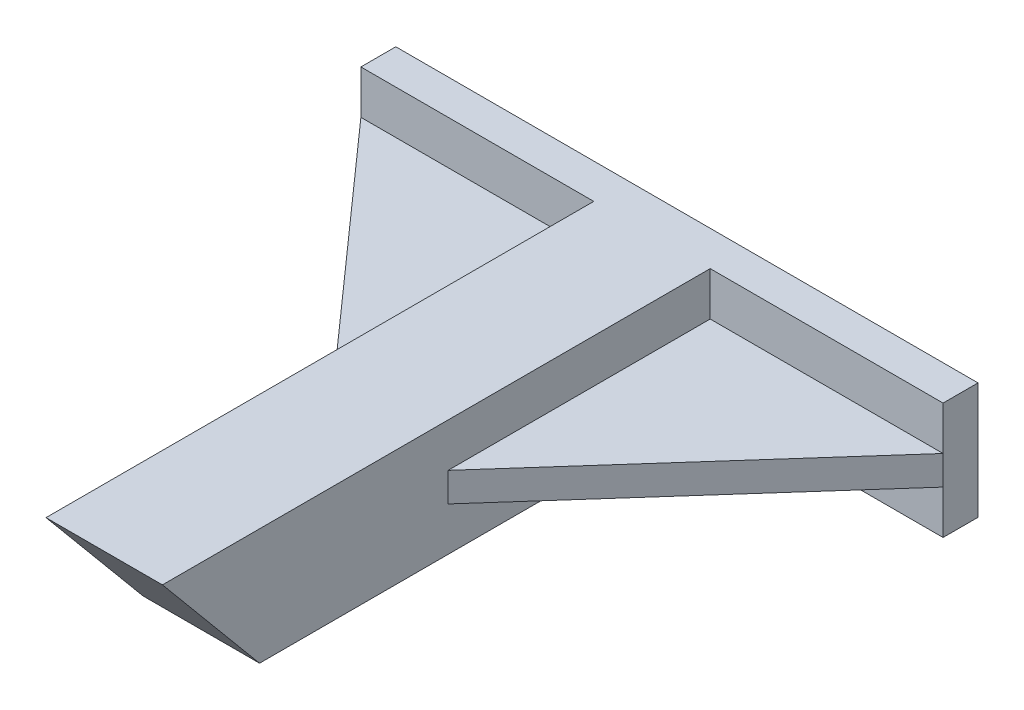
SolidWorks part; units mm, degrees
ref_plane "Ebene vorne" through (0, 0, 0) normal (1, 0, 0) x (0, 1, 0)
ref_plane "Ebene oben" through (0, 0, 0) normal (0, 0, 1) x (0, 1, 0)
ref_plane "Ebene rechts" through (0, 0, 0) normal (0, 1, 0) x (-1, 0, 0)
sketch "Skizze1" plane through (0, 0, 0) normal (-1, 0, 0) x (0, 0, 1)
  line L0 (163.02, 105.5331) -> (34.515, -48.5402) construction
  line L1 (75, 100) -> (75, 120)
  line L2 (75, 300) -> (75, 0) construction
  line L3 (75, 120) -> (175.0861, 120)
  line L4 (175.0861, 120) -> (158.405, 100)
  line L5 (75, 100) -> (158.405, 100)
  line L6 (-56.5, 272.5) -> (56.5, 210.5) construction
  line L7 (0, 241.5) -> (163.02, 105.5331) construction
  line L8 (35, 120) -> (73.2, 120) construction
  line L10 (-56.5, 210.5) -> (56.5, 210.5)
  line L11 (56.5, 210.5) -> (56.5, 272.5)
  line L12 (56.5, 272.5) -> (-56.5, 272.5)
  line L13 (-56.5, 272.5) -> (-56.5, 210.5)
  line L14 (-56.5, 210.5) -> (56.5, 210.5) construction
  line L15 (56.5, 210.5) -> (56.5, 272.5) construction
  line L16 (56.5, 272.5) -> (-56.5, 272.5) construction
  line L17 (-56.5, 272.5) -> (-56.5, 210.5) construction
  circle A0 centre (0, -13) radius 49.2697 construction
  dimension "D1" = 20
  dimension "D2" = 0
extrude "Aufsatz-Linear austragen1" add sketch "Skizze1" against normal blind 20
sketch "Skizze2" plane through (0, 120, 0) normal (0, 1, 0) x (1, 0, 0)
  line L0 (-130, -75) -> (130, -75) construction
  line L1 (-40, -75) -> (60, -75)
  line L2 (-40, -75) -> (-40, -81)
  line L3 (-40, -81) -> (60, -81)
  line L4 (60, -75) -> (60, -81)
  line L5 (10, -175.0861) -> (10, -81) construction
  line L6 (20, -175.0861) -> (0, -175.0861) construction
  dimension "D1" = 6
  dimension "D2" = 100
extrude "Aufsatz-Linear austragen2" add sketch "Skizze2" against normal blind 20
ref_plane "Ebene1" through (0, 110, 0) normal (0, 1, 0) x (1, 0, 0)
sketch "Skizze3" plane through (0, 110, 0) normal (0, 1, 0) x (1, 0, 0)
  line L0 (-40, -81) -> (0, -126.0181)
  line L1 (0, -126.0181) -> (20, -126.0181)
  line L2 (20, -175.0861) -> (20, -81) construction
  line L3 (20, -126.0181) -> (60, -81)
  line L4 (60, -81) -> (-40, -81)
extrude "Aufsatz-Linear austragen3" add sketch "Skizze3" along normal mid plane 5
